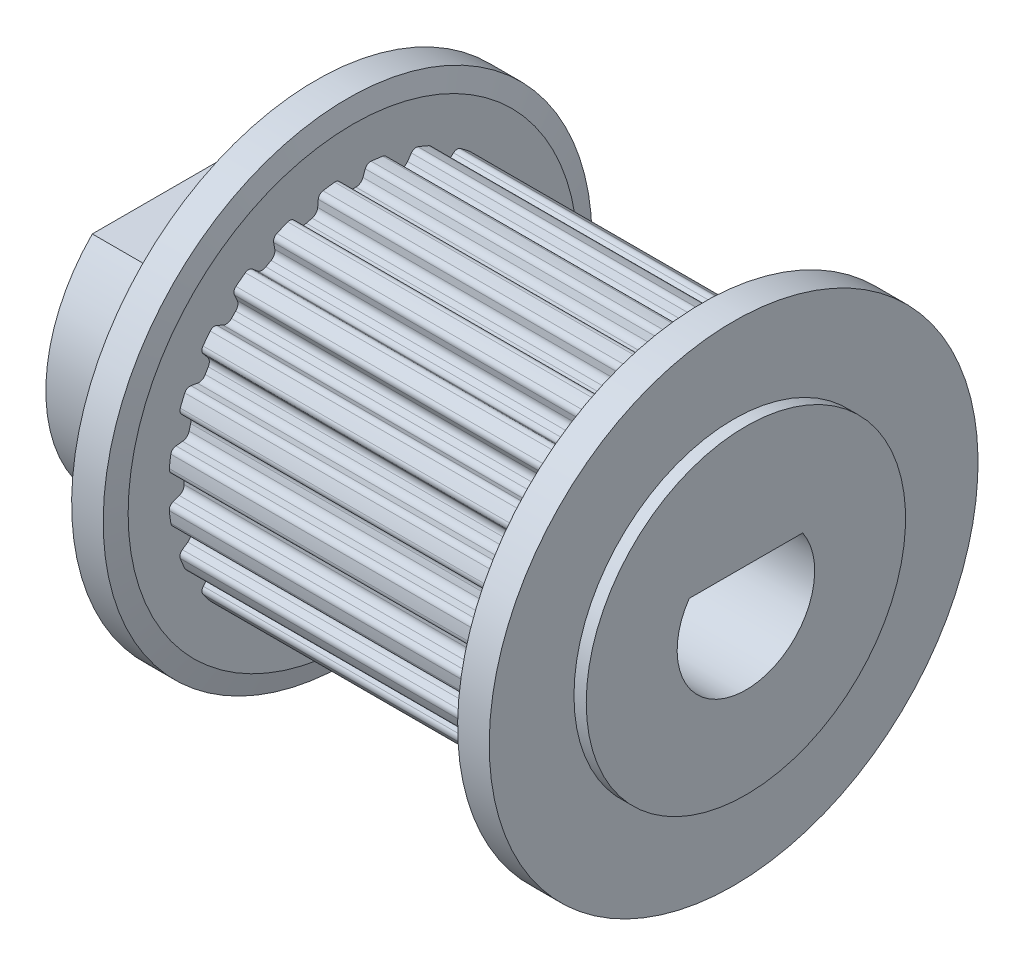
SolidWorks part; units mm, degrees
ref_plane "前视基准面" through (0, 0, 0) normal (0, 0, 1) x (1, 0, 0)
ref_plane "上视基准面" through (0, 0, 0) normal (0, 1, 0) x (1, 0, 0)
ref_plane "右视基准面" through (0, 0, 0) normal (1, 0, 0) x (0, 0, -1)
sketch "草图1" plane through (0, 0, 0) normal (0, 0, 1) x (1, 0, 0)
  line L0 (-9, 6.5) -> (-7, 6.5)
  line L1 (-7, 6.5) -> (-7, 7.51)
  line L2 (-7, 7.51) -> (7, 7.51)
  line L3 (0, 0) -> (0, 7.51) construction
  line L4 (-9, 6.5) -> (-9, 0)
  line L5 (9, 6.5) -> (9, 0)
  line L6 (7, 6.5) -> (7, 7.51)
  line L7 (9, 6.5) -> (7, 6.5)
  line L8 (-9, 0) -> (9, 0)
  dimension "D1" = 6.5
  dimension "D2" = 7.51
  dimension "D3" = 14
  dimension "D4" = 18
revolve "旋转1" add sketch "草图1" angle 360 about L8
sketch "草图3" plane through (0, 0, 0) normal (1, 0, 0) x (0, 0, -1)
  line L0 (0, 0) -> (0, 7.51) construction
  line L1 (-0.335, 6.8618) -> (-0.5632, 7.4889)
  line L2 (0.5632, 7.4889) -> (0.335, 6.8618)
  arc A0 (0.5632, 7.4889) -> (-0.5632, 7.4889) centre (0, 0) ccw
  circle A1 centre (0, 0) radius 7.51 construction
  arc A2 (0.335, 6.8618) -> (-0.335, 6.8618) centre (0, 0) ccw
  dimension "D4" = 0.64
  dimension "D1" = 0.67
  dimension "D2" = 20
  dimension "D3" = 20
extrude "切除-拉伸3" cut sketch "草图3" against normal mid plane 14
fillet "圆角3" radius 0.23 2 edges at (0, 7.4889, -0.5632) (0, 7.4889, 0.5632)
fillet "圆角4" radius 0.3 2 edges at (0, 6.8618, -0.335) (0, 6.8618, 0.335)
pattern_circular "阵列(圆周)2" count 24 over 360 about axis through (0, 0, 0) along (1, 0, 0) of "圆角3", "切除-拉伸3", "圆角4"
sketch "草图4" plane through (0, 0, 0) normal (0, 0, 1) x (1, 0, 0)
  line L0 (-8.5, 9.95) -> (-8.5, 6.5)
  line L1 (-7, 6.5) -> (-9, 6.5) construction
  line L2 (8.5, 9.95) -> (8.5, 6.5)
  line L3 (-8.5, 9.95) -> (-7.2144, 9.95)
  line L4 (-7.2144, 9.95) -> (-7, 9.15)
  line L5 (-7, 9.15) -> (-7, 6.5)
  line L6 (-7, 6.5) -> (-8.5, 6.5)
  line L7 (-7, 7.51) -> (-7, -7.51) construction
  line L9 (0, 0) -> (0, 9.52) construction
  line L11 (-9, 0) -> (9, 0) construction
  line L12 (-9, 6.5) -> (-9, -6.5) construction
  line L13 (9, -6.5) -> (9, 6.5) construction
  line L14 (7, 9.15) -> (7, 6.5)
  line L15 (7, 6.5) -> (8.5, 6.5)
  line L17 (7.2144, 9.95) -> (7, 9.15)
  line L18 (8.5, 9.95) -> (7.2144, 9.95)
  dimension "D1" = 1.5
  dimension "D2" = 15
  dimension "D3" = 9.95
  dimension "D4" = 0.8
revolve "旋转2" add sketch "草图4" angle 360 about L11
sketch "草图5" plane through (0, 0, 0) normal (0, 0, 1) x (1, 0, 0)
  line L0 (9, -6.5) -> (9, 6.5) construction
  line L1 (9, 0) -> (15.5, 0)
  line L2 (9, 0) -> (9, 5.5)
  line L3 (9, 5.5) -> (15.5, 5.5)
  line L4 (15.5, 0) -> (15.5, 5.5)
  dimension "D1" = 5.5
  dimension "D2" = 6.5
revolve "旋转3" [suppressed] add sketch "草图5" angle 360 about L1
sketch "草图37" [suppressed] plane through (0, 0, 0) normal (0, 0, 1) x (1, 0, 0)
  line L0 (-5, 0) -> (5, 0) construction
  line L1 (-5, 8.95) -> (-3, 8.95)
  line L2 (-5, 8.95) -> (-5, 5.5)
  line L3 (-5, 5.5) -> (-3, 5.5)
  line L4 (-3, 8.95) -> (-3, 5.5)
  line L5 (-5, 5.5) -> (-5, -5.5) construction
  line L6 (5, -5.5) -> (5, 5.5) construction
  line L7 (0, 0) -> (0, 7.8967) construction
  line L8 (3, 8.95) -> (3, 5.5)
  line L9 (5, 5.5) -> (3, 5.5)
  line L10 (5, 8.95) -> (3, 8.95)
  line L11 (5, 8.95) -> (5, 5.5)
  dimension "D1" = 7
  dimension "D2" = 6.5
  dimension "D3" = 9.95
  dimension "D4" = 2
revolve "切除-旋转5" [suppressed] cut sketch "草图37" angle 360 about L0
sketch "草图6" [suppressed] plane through (0, 0, 0) normal (0, 0, 1) x (1, 0, 0)
  line L0 (-4.5, 5.95) -> (-4.5, 3)
  line L1 (-3, 3) -> (-5, 3) construction
  line L3 (-4.5, 5.95) -> (-3.2144, 5.95)
  line L4 (-3.2144, 5.95) -> (-3, 5.15)
  line L5 (-3, 5.15) -> (-3, 3)
  line L6 (-3, 3) -> (-4.5, 3)
  line L8 (3, 0) -> (3, 5.15)
  line L9 (3, 5.15) -> (3.2278, 6)
  line L10 (3.2278, 6) -> (11.5, 6)
  line L11 (11.5, 6) -> (11.5, 0)
  line L12 (11.5, 0) -> (3, 0)
  line L14 (-5, 0) -> (5, 0) construction
  line L15 (-5, 3) -> (-5, -3) construction
  line L16 (5, -3) -> (5, 3) construction
  dimension "D1" = 1.5
  dimension "D2" = 15
  dimension "D3" = 0.8
  dimension "D4" = 9.95
  dimension "D5" = 5.5
  dimension "D6" = 15
  dimension "D7" = 16.5
  dimension "D8" = 7
revolve "旋转4" [suppressed] add sketch "草图6" angle 360 about L14
sketch "草图7" plane through (-9, 0, 0) normal (-1, 0, 0) x (0, 0, 1)
  circle A0 centre (0, 0) radius 2.5
  dimension "D1" = 5
extrude "切除-拉伸4" cut sketch "草图7" against normal through all
sketch "草图31" [suppressed] plane through (0, 0, 0) normal (0, 1, 0) x (1, 0, 0)
  circle A0 centre (8.5, 0) radius 1.29
  dimension "D2" = 2.58
  dimension "D1" = 8.5
extrude "切除-拉伸21" [suppressed] cut sketch "草图31" along normal through all
cosmetic thread "装饰螺纹线9" [suppressed] parameters "D2"=3
sketch "草图32" [suppressed] plane through (0, 0, 0) normal (0, 1, 0) x (1, 0, 0)
  line L0 (0, 0) -> (-5, 0) construction
  line L1 (-5, 5.5) -> (-5, -5.5) construction
ref_plane "基准面5" [suppressed] through (0, 0, 0) normal (0, -0.5, -0.866) x (1, 0, 0)
sketch "草图33" [suppressed] plane through (0, 0, 0) normal (0, -0.5, -0.866) x (1, 0, 0)
  circle A0 centre (8.5, 0) radius 1.29
  dimension "D2" = 2.58
  dimension "D1" = 8.5
extrude "切除-拉伸22" [suppressed] cut sketch "草图33" along normal through all
cosmetic thread "装饰螺纹线10" [suppressed] parameters "D2"=3
sketch "草图16" [suppressed] plane through (-5, 0, 0) normal (-1, 0, 0) x (0, 0, 1)
  line L0 (-1.5, 0) -> (-1.5, 2.9)
  line L1 (-1.5, 2.9) -> (1.5, 2.9)
  line L2 (1.5, 2.9) -> (1.5, 0)
  arc A0 (-1.5, 0) -> (1.5, 0) centre (0, 0) ccw
  dimension "D2" = 2.5
  dimension "D1" = 3
  dimension "D3" = 3.9
extrude "切除-拉伸10" [suppressed] cut sketch "草图16" against normal through all
sketch "草图27" [suppressed] plane through (11.5, 0, 0) normal (1, 0, 0) x (0, 0, -1)
  circle A0 centre (0, 0) radius 5
  dimension "D1" = 10
extrude "切除-拉伸19" [suppressed] cut sketch "草图27" against normal blind 5
sketch "草图29" [suppressed] plane through (0, 0, 0) normal (0, 0, 1) x (1, 0, 0)
  line L0 (-5, 5) -> (-2, 5)
  line L1 (-5, 8) -> (-5, -8) construction
  line L2 (-2, 5) -> (-2, 4)
  line L3 (-2, 4) -> (2, 4)
  line L4 (2, 4) -> (2, 5)
  line L5 (2, 5) -> (5, 5)
  line L6 (5, -8) -> (5, 8) construction
  line L7 (5, 5) -> (5, 0)
  line L8 (5, 0) -> (-5, 0)
  line L9 (-5, 0) -> (-5, 5)
  dimension "D1" = 4.5
  dimension "D2" = 3
  dimension "D3" = 3
  dimension "D4" = 5
  dimension "D5" = 2.5
revolve "切除-旋转1" [suppressed] cut sketch "草图29" angle 360 about L8
sketch "草图38" plane through (0, 0, 0) normal (0, 0, 1) x (1, 0, 0)
  line L0 (-9, 6.5) -> (-9, -6.5) construction
  line L1 (-9, 0) -> (-4, 0)
  line L2 (-9, 0) -> (-9, 5)
  line L3 (-9, 5) -> (-4, 5)
  line L4 (-4, 0) -> (-4, 5)
  dimension "D1" = 5
  dimension "D2" = 5
revolve "切除-旋转6" [suppressed] cut sketch "草图38" angle 360 about L1
sketch "草图36" [suppressed] plane through (0, 0, 0) normal (0, 0, 1) x (1, 0, 0)
  line L0 (0, 0) -> (-5, 0) construction
  line L1 (-3, 4.275) -> (-5, 4.275)
  line L2 (-3, 4.275) -> (-3, 5.95)
  line L3 (-3, 5.95) -> (-5, 5.95)
  line L4 (-5, 4.275) -> (-5, 5.95)
  line L5 (-5, 3) -> (-5, -3) construction
  dimension "D1" = 7.51
  dimension "D2" = 9.95
  dimension "D3" = 7
  dimension "D4" = 2
revolve "切除-旋转4" [suppressed] cut sketch "草图36" angle 360 about L0
sketch "草图35" [suppressed] plane through (0, 0, 0) normal (0, 0, 1) x (1, 0, 0)
  line L0 (-5, 0) -> (0, 0) construction
  line L1 (3, 4.275) -> (5, 4.275)
  line L2 (3, 4.275) -> (3, 5.95)
  line L3 (3, 5.95) -> (5, 5.95)
  line L4 (5, 4.275) -> (5, 5.95)
  line L5 (-5, 3) -> (-5, -3) construction
  dimension "D1" = 7.51
  dimension "D2" = 9.95
  dimension "D3" = 2
  dimension "D4" = 7
revolve "切除-旋转3" [suppressed] cut sketch "草图35" angle 360 about L0
sketch "草图39" [suppressed] plane through (0, 0, 0) normal (0, 0, 1) x (1, 0, 0)
  line L0 (-1000, 0) -> (49000, 0) construction
  line L1 (4.5, -8.95) -> (4.5, 8.95) construction
  line L2 (-4.5, 8.95) -> (4.5, 8.95)
  line L3 (-4.5, 8.95) -> (-4.5, 8)
  line L4 (-4.5, 8) -> (4.5, 8)
  line L5 (4.5, 8.95) -> (4.5, 8)
  dimension "D1" = 8
revolve "切除-旋转7" [suppressed] cut sketch "草图39" angle 360 about L0
sketch "草图40" [suppressed] plane through (0, 0, 0) normal (0, 0, 1) x (1, 0, 0)
  line L0 (11.5, 4.29) -> (5.5, 4.29)
  line L1 (11.5, -4.5) -> (11.5, 4.5) construction
  line L2 (5.5, 4.29) -> (4.7249, 3)
  line L3 (4.7249, 3) -> (11.5, 3)
  line L4 (11.5, 3) -> (11.5, 4.29)
  dimension "D1" = 59
  dimension "D2" = 1.29
  dimension "D3" = 6
  dimension "D4" = 3
revolve "切除-旋转8" [suppressed] cut sketch "草图40" angle 360 about L3
cosmetic thread "装饰螺纹线11" [suppressed] parameters "D2"=3
pattern_circular "阵列(圆周)3" [suppressed] count 4 over 360
sketch "草图41" [suppressed] plane through (0, 0, 0) normal (0, 0, 1) x (1, 0, 0)
  line L0 (11.5, 4.29) -> (5.5, 4.29)
  line L1 (11.5, -4.5) -> (11.5, 4.5) construction
  line L2 (5.5, 4.29) -> (4.7249, 3)
  line L3 (4.7249, 3) -> (11.5, 3)
  line L4 (11.5, 3) -> (11.5, 4.29)
  dimension "D1" = 59
  dimension "D2" = 3
  dimension "D3" = 1.29
  dimension "D4" = 6
revolve "切除-旋转9" [suppressed] cut sketch "草图41" angle 360 about L3
cosmetic thread "装饰螺纹线12" [suppressed] parameters "D2"=3
pattern_circular "阵列(圆周)4" [suppressed] count 3 over 360
sketch "草图42" [suppressed] plane through (0, 0, 0) normal (0, 0, 1) x (1, 0, 0)
  line L0 (11.5, 4.29) -> (5.5, 4.29)
  line L1 (11.5, -4.5) -> (11.5, 4.5) construction
  line L2 (5.5, 4.29) -> (4.7249, 3)
  line L3 (4.7249, 3) -> (11.5, 3)
  line L4 (11.5, 3) -> (11.5, 4.29)
  dimension "D1" = 59
  dimension "D2" = 3
  dimension "D3" = 1.29
  dimension "D4" = 6
revolve "切除-旋转10" [suppressed] cut sketch "草图42" angle 360 about L3
cosmetic thread "装饰螺纹线13" [suppressed] parameters "D2"=3
pattern_circular "阵列(圆周)5" [suppressed] count 6 over 360
sketch "草图43" [suppressed] plane through (0, 0, 0) normal (0, 0, 1) x (1, 0, 0)
  line L0 (11.5, -4.55) -> (11.5, 4.55) construction
  line L1 (11.5, 3) -> (-5, 3)
  line L2 (11.5, 3) -> (11.5, 4.5)
  line L3 (11.5, 4.5) -> (-5, 4.5)
  line L4 (-5, 3) -> (-5, 4.5)
  line L5 (-5, 5.5) -> (-5, -5.5) construction
  dimension "D1" = 3
  dimension "D2" = 1.5
revolve "切除-旋转12" [suppressed] cut sketch "草图43" angle 360 about L1
pattern_circular "阵列(圆周)6" [suppressed] count 4 over 360
sketch "草图44" [suppressed] plane through (0, 0, 0) normal (0, 0, 1) x (1, 0, 0)
  line L0 (11.5, -4.55) -> (11.5, 4.55) construction
  line L1 (11.5, 3) -> (-5, 3)
  line L2 (11.5, 3) -> (11.5, 4.5)
  line L3 (11.5, 4.5) -> (-5, 4.5)
  line L4 (-5, 3) -> (-5, 4.5)
  line L5 (-5, 5.5) -> (-5, -5.5) construction
  dimension "D1" = 3
  dimension "D2" = 1.5
revolve "切除-旋转13" [suppressed] cut sketch "草图44" angle 360 about L1
pattern_circular "阵列(圆周)7" [suppressed] count 3 over 360
sketch "草图45" [suppressed] plane through (0, 0, 0) normal (0, 0, 1) x (1, 0, 0)
  line L0 (11.5, -4.55) -> (11.5, 4.55) construction
  line L1 (11.5, 3) -> (-5, 3)
  line L2 (11.5, 3) -> (11.5, 4.45)
  line L3 (11.5, 4.45) -> (-5, 4.45)
  line L4 (-5, 3) -> (-5, 4.45)
  line L5 (-5, 5.5) -> (-5, -5.5) construction
  dimension "D1" = 3
  dimension "D2" = 1.45
revolve "切除-旋转14" [suppressed] cut sketch "草图45" angle 360 about L1
pattern_circular "阵列(圆周)12" [suppressed] count 6 over 360
sketch "草图46" [suppressed] plane through (0, 0, 0) normal (0, 0, 1) x (1, 0, 0)
  line L0 (-5, 4.65) -> (8, 4.65)
  line L1 (-5, 5.5) -> (-5, -5.5) construction
  line L2 (8, 4.65) -> (8, 6.25)
  line L3 (8, 6.25) -> (11.5, 6.25)
  line L4 (11.5, -4.55) -> (11.5, 4.55) construction
  line L5 (11.5, 6.25) -> (11.5, 3)
  line L6 (11.5, 3) -> (-5, 3)
  line L7 (-5, 3) -> (-5, 4.65)
  dimension "D1" = 3
  dimension "D2" = 1.65
  dimension "D3" = 3.25
  dimension "D4" = 3.5
revolve "切除-旋转15" [suppressed] cut sketch "草图46" angle 360 about L6
pattern_circular "阵列(圆周)13" [suppressed] count 4 over 360
sketch "草图47" [suppressed] plane through (0, 0, 0) normal (0, 0, 1) x (1, 0, 0)
  line L0 (-5, 4.65) -> (8, 4.65)
  line L1 (-5, 5.5) -> (-5, -5.5) construction
  line L2 (8, 4.65) -> (8, 6.25)
  line L3 (8, 6.25) -> (11.5, 6.25)
  line L4 (11.5, -4.55) -> (11.5, 4.55) construction
  line L5 (11.5, 6.25) -> (11.5, 3)
  line L6 (11.5, 3) -> (-5, 3)
  line L7 (-5, 3) -> (-5, 4.65)
  dimension "D1" = 3
  dimension "D2" = 1.65
  dimension "D3" = 3.25
  dimension "D4" = 3.5
revolve "切除-旋转16" [suppressed] cut sketch "草图47" angle 360 about L6
pattern_circular "阵列(圆周)14" [suppressed] count 3 over 360
sketch "草图48" [suppressed] plane through (0, 0, 0) normal (0, 0, 1) x (1, 0, 0)
  line L0 (-5, 4.65) -> (8, 4.65)
  line L1 (-5, 5.5) -> (-5, -5.5) construction
  line L2 (8, 4.65) -> (8, 6.25)
  line L3 (8, 6.25) -> (11.5, 6.25)
  line L4 (11.5, -4.55) -> (11.5, 4.55) construction
  line L5 (11.5, 6.25) -> (11.5, 3)
  line L6 (11.5, 3) -> (-5, 3)
  line L7 (-5, 3) -> (-5, 4.65)
  dimension "D1" = 3
  dimension "D2" = 1.65
  dimension "D3" = 3.25
  dimension "D4" = 3.5
revolve "切除-旋转17" [suppressed] cut sketch "草图48" angle 360 about L6
pattern_circular "阵列(圆周)15" [suppressed] count 6 over 360
sketch "Sketch1" plane through (-9, 0, 0) normal (-1, 0, 0) x (0, 0, 1)
  line B0 (1.5347, 1.2825) -> (-1.5357, 1.2812)
  line B1 (-2.1469, 1.281) -> (2.1458, 1.2827)
  line B2 (-1.5357, 1.2812) -> (-2.1469, 1.281)
  line B3 (-1.5357, 1.2812) -> (-2.1469, 1.281)
  line B4 (-2.1469, 1.281) -> (2.1458, 1.2827)
  line B5 (-1.5357, 1.2812) -> (-2.1469, 1.281)
  arc B6 (2.1458, 1.2827) -> (-2.1469, 1.281) centre (0, 0) ccw
  arc B7 (-2.1469, 1.281) -> (2.1458, 1.2827) centre (0, 0) ccw
  arc B8 (-1.5357, 1.2812) -> (1.5347, 1.2825) centre (0, 0) ccw
  arc B9 (-2.1469, 1.281) -> (2.1458, 1.2827) centre (0, 0) ccw
  arc B10 (-1.5357, 1.2812) -> (1.5347, 1.2825) centre (0, 0) ccw
  arc B11 (2.1458, 1.2827) -> (-2.1469, 1.281) centre (0, 0) ccw
  arc B12 (-2.1469, 1.281) -> (2.1458, 1.2827) centre (0, 0) ccw
  arc B13 (-1.5357, 1.2812) -> (1.5347, 1.2825) centre (0, 0) ccw
sketch_block_instance "Stepper_Shaft_D_Profile-1"
sketch_block "Stepper_Shaft_D_Profile"
sketch "Sketch2" plane through (-9, 0, 0) normal (-1, 0, 0) x (0, 0, 1)
  arc A0 (-2.1469, 1.281) -> (2.1458, 1.2827) centre (0, 0) ccw construction
  circle A1 centre (0, 0) radius 6.5
  circle A2 centre (0, 0) radius 6.5
  arc A3 (2.1458, 1.2827) -> (-2.1469, 1.281) centre (0, 0) ccw construction
  arc A4 (-2.1469, 1.281) -> (2.1458, 1.2827) centre (0, 0) ccw
  arc A5 (2.1458, 1.2827) -> (-2.1469, 1.281) centre (0, 0) ccw
  arc A6 (2.4033, 1.4367) -> (-2.4045, 1.4347) centre (0, 0) ccw
  arc A7 (-2.4045, 1.4347) -> (2.4033, 1.4367) centre (0, 0) ccw
  circle M4 centre (0, 0) radius 2.5
  dimension "D1" = 0
  dimension "D2" = 0.3
extrude "Cut-Extrude1" cut sketch "Sketch2" against normal through all contours A6 A7 M4 | M4
sketch "Sketch3" plane through (-9, 0, 0) normal (-1, 0, 0) x (0, 0, 1)
  circle A0 centre (0, 0) radius 6.5 construction
  circle A1 centre (0, 0) radius 6.5
extrude "Boss-Extrude1" add sketch "Sketch3" along normal blind 4 contours A1
sketch "Sketch4" plane through (-13, 0, 0) normal (-1, 0, 0) x (0, 0, 1)
  arc A4 (-2.4045, 1.4347) -> (2.4033, 1.4367) centre (0, 0) ccw
  arc A5 (2.4033, 1.4367) -> (-2.4045, 1.4347) centre (0, 0) ccw
  arc A6 (-2.4045, 1.4347) -> (2.4033, 1.4367) centre (0, 0) ccw
  arc A7 (2.4033, 1.4367) -> (-2.4045, 1.4347) centre (0, 0) ccw
  dimension "D1" = 0.3
extrude "Cut-Extrude2" cut sketch "Sketch4" against normal through all
sketch "Sketch5" plane through (-13, 0, 0) normal (-1, 0, 0) x (0, 0, 1)
  line L2 (2.3097, 1.5828) -> (-2.311, 1.5809)
  line L3 (1.9353, 1.5826) -> (-1.9366, 1.5811) construction
  line L4 (2.4888, 1.2829) -> (-2.4899, 1.2808) construction
  circle A0 centre (0, 0) radius 2.8 construction
  arc A3 (2.3097, 1.5828) -> (-2.311, 1.5809) centre (0, 0) ccw
  arc A4 (1.9353, 1.5826) -> (-1.9366, 1.5811) centre (0, 0) ccw construction
  arc A5 (2.4888, 1.2829) -> (-2.4899, 1.2808) centre (0, 0) ccw construction
  dimension "D1" = 0.3
extrude "Boss-Extrude2" add sketch "Sketch5" against normal up to surface (22 mm away) contours L2 A3 up to face at (9, 0, 2.8)
sketch "Sketch6" plane through (-13, 0, 0) normal (-1, 0, 0) x (0, 0, 1)
  line L2 (2.3085, 4.5828) -> (-2.3122, 4.5809)
  line L3 (4.6086, 4.5837) -> (-4.6124, 4.58)
  circle A0 centre (0, 0) radius 6.5 construction
  arc A1 (4.6086, 4.5837) -> (-4.6124, 4.58) centre (0, 0) ccw
  dimension "D1" = 3
extrude "Cut-Extrude3" cut sketch "Sketch6" against normal up to surface (4.5 mm away) up to face at (-8.5, 6.5, 0)
sketch "Sketch7" plane through (0, 4.5819, -0.0019) normal (0, 1, -0.0004) x (1, 0, 0)
  line L0 (-10.9663, 4.6105) -> (-10.75, -4.6105)
  line L1 (-8.5, 4.6105) -> (-13, 4.6105) construction
  line L2 (-8.5, -4.6105) -> (-13, -4.6105) construction
  line L3 (-8.5, 0) -> (-13, 0)
  line L4 (-8.5, 4.6105) -> (-8.5, -4.6105) construction
  line L5 (-13, 4.6105) -> (-13, -4.6105) construction
  circle A0 centre (-10.8581, 0) radius 0.3533
extrude "Cut-Extrude4" cut sketch "Sketch7" against normal blind 0.1 contours A0
